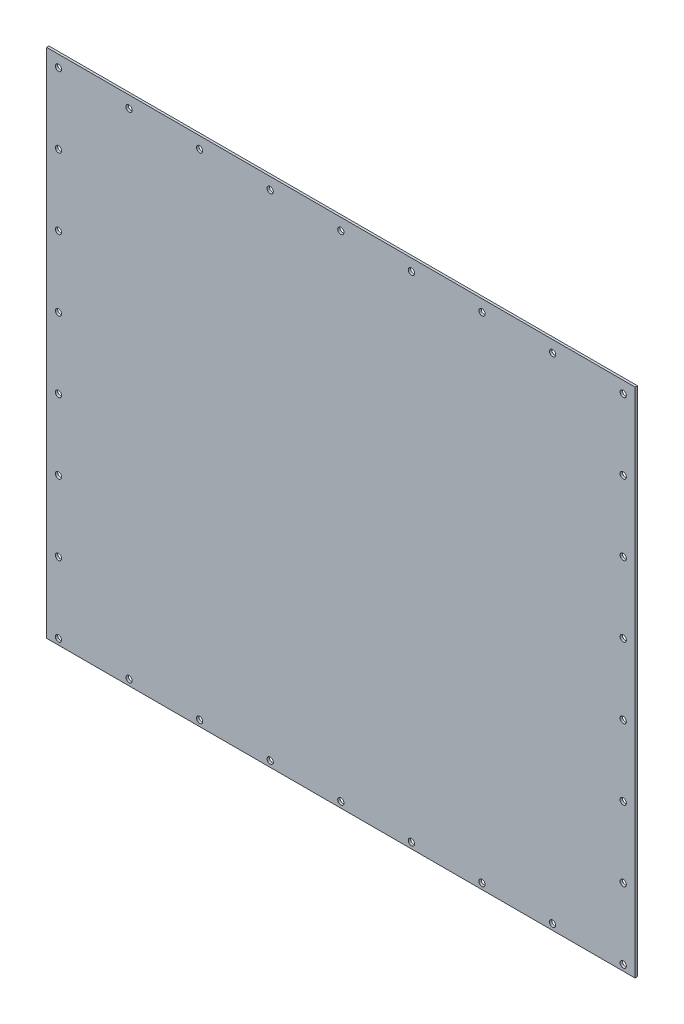
SolidWorks part; units mm, degrees
material "AISI 304"
ref_plane "Front Plane" through (0, 0, 0) normal (0, 0, 1) x (1, 0, 0)
ref_plane "Top Plane" through (0, 0, 0) normal (0, 1, 0) x (1, 0, 0)
ref_plane "Right Plane" through (0, 0, 0) normal (1, 0, 0) x (0, 0, -1)
sketch "Sketch1" plane through (0, 0, 0) normal (0, 0, 1) x (1, 0, 0)
  line L1 (250, -250) -> (-250, -250)
  line L2 (250, -250) -> (250, 250)
  line L3 (250, 250) -> (-250, 250)
  line L4 (-250, -250) -> (-250, 250)
  line L5 (250, -250) -> (-250, 250) construction
  line L6 (250, 250) -> (-250, -250) construction
  point P0 (0, 0)
  dimension "D1" = 500
  dimension "D2" = 500
extrude "Boss-Extrude1" add sketch "Sketch1" along normal mid plane 2
hole_wizard "M5 Clearance Hole2" positions "Sketch2" profile "Sketch3" hole size "M5" standard "ANSI Metric"
sketch "Sketch2" plane through (0, 0, 1) normal (0, 0, 1) x (1, 0, 0)
  line L1 (240, -245) -> (-240, -245)
  line L2 (240, -245) -> (240, 175)
  line L3 (240, 175) -> (-240, 175)
  line L4 (-240, -245) -> (-240, 175)
  line L5 (240, -245) -> (-240, 175) construction
  line L6 (240, 175) -> (-240, -245) construction
  line L7 (-250, -250) -> (250, -250) construction
  line L8 (-250, 250) -> (-250, -250) construction
  line L9 (0, -35) -> (0, -245) construction
  line L10 (250, 250) -> (-250, 250) construction
  point P137 (-240, -245)
  point P142 (0, -35)
  dimension "D1" = 5
  dimension "D2" = 10
  dimension "D3" = 75
sketch "Sketch3" plane through (-240, -245, 1) normal (1, 0, 0) x (0, -1, 0)
  line L0 (0, 0) -> (0, 9.5923)
  line L1 (0, 9.5923) -> (2.65, 8)
  line L2 (2.65, 8) -> (2.65, 0)
  line L5 (2.65, 0) -> (0, 0)
  line L10 (0, 9.5923) -> (-2.65, 8) construction
  line L11 (0, -6.35) -> (0, 107.95) construction
  dimension "Hole Dia." = 5.3
  dimension "Hole Depth" = 8
  dimension "Drill Angle" = 118
sketch "Sketch4" plane through (0, 0, 1) normal (0, 0, 1) x (1, 0, 0)
  line L0 (-242.65, -245) -> (-242.65, -250)
  line L1 (-250, -250) -> (250, -250) construction
  line L2 (-242.65, -250) -> (-237.35, -250)
  line L3 (-237.35, -250) -> (-237.35, -245)
  circle A0 centre (-240, -245) radius 2.65 construction
  arc A1 (-242.65, -245) -> (-237.35, -245) centre (-240, -245) ccw
extrude "Cut-Extrude1" [suppressed] cut sketch "Sketch4" against normal up to surface (2 mm away)
pattern_linear "LPattern1" count 9 spacing 60 along (1, 0, 0) of "M5 Clearance Hole2"
fillet "Fillet1" [suppressed] radius 1
hole_wizard "M5 Clearance Hole1" positions "Sketch5" profile "Sketch6" hole size "M5" standard "ANSI Metric"
sketch "Sketch5" plane through (0, 0, 1) normal (0, 0, 1) x (1, 0, 0)
  point P0 (-240, 175)
sketch "Sketch6" plane through (-240, 175, 1) normal (1, 0, 0) x (0, -1, 0)
  line L0 (0, 0) -> (0, 9.5923)
  line L1 (0, 9.5923) -> (2.65, 8)
  line L2 (2.65, 8) -> (2.65, 0)
  line L5 (2.65, 0) -> (0, 0)
  line L10 (0, 9.5923) -> (-2.65, 8) construction
  line L11 (0, -6.35) -> (0, 107.95) construction
  dimension "Hole Dia." = 5.3
  dimension "Hole Depth" = 8
  dimension "Drill Angle" = 118
pattern_linear "LPattern2" count 9 spacing 60 along (1, 0, 0) of "M5 Clearance Hole1"
sketch "Sketch7" plane through (0, 0, 1) normal (0, 0, 1) x (1, 0, 0)
  line L0 (-240, 177.65) -> (-250, 177.65)
  line L1 (-250, 250) -> (-250, -250) construction
  line L2 (-250, 177.65) -> (-250, 172.35)
  line L3 (-250, 172.35) -> (-240, 172.35)
  circle A0 centre (-240, 175) radius 2.65 construction
  arc A1 (-240, 177.65) -> (-240, 172.35) centre (-240, 175) ccw
extrude "Cut-Extrude2" [suppressed] cut sketch "Sketch7" against normal up to surface (2 mm away)
pattern_linear "LPattern3" count 8 spacing 60 along (0, -1, 0) count 2 spacing 60 along (0, 1, 0) of "M5 Clearance Hole1"
mirror "Mirror1" about plane through (0, 0, 0) normal (1, 0, 0) of "LPattern3"
fillet "Fillet2" [suppressed] radius 1
sketch "Sketch8" plane through (0, 0, 1) normal (0, 0, 1) x (1, 0, 0)
  line L0 (250, -250) -> (250, 250) construction
  line L1 (-250, 250) -> (250, 250)
  line L2 (-250, 250) -> (-250, 185)
  line L3 (-250, 185) -> (250, 185)
  line L4 (250, 250) -> (250, 185)
  circle A0 centre (240, 175) radius 2.65 construction
  dimension "D1" = 10
extrude "Cut-Extrude3" cut sketch "Sketch8" against normal up to surface (2 mm away) up to face at (242.65, -185, -1)
